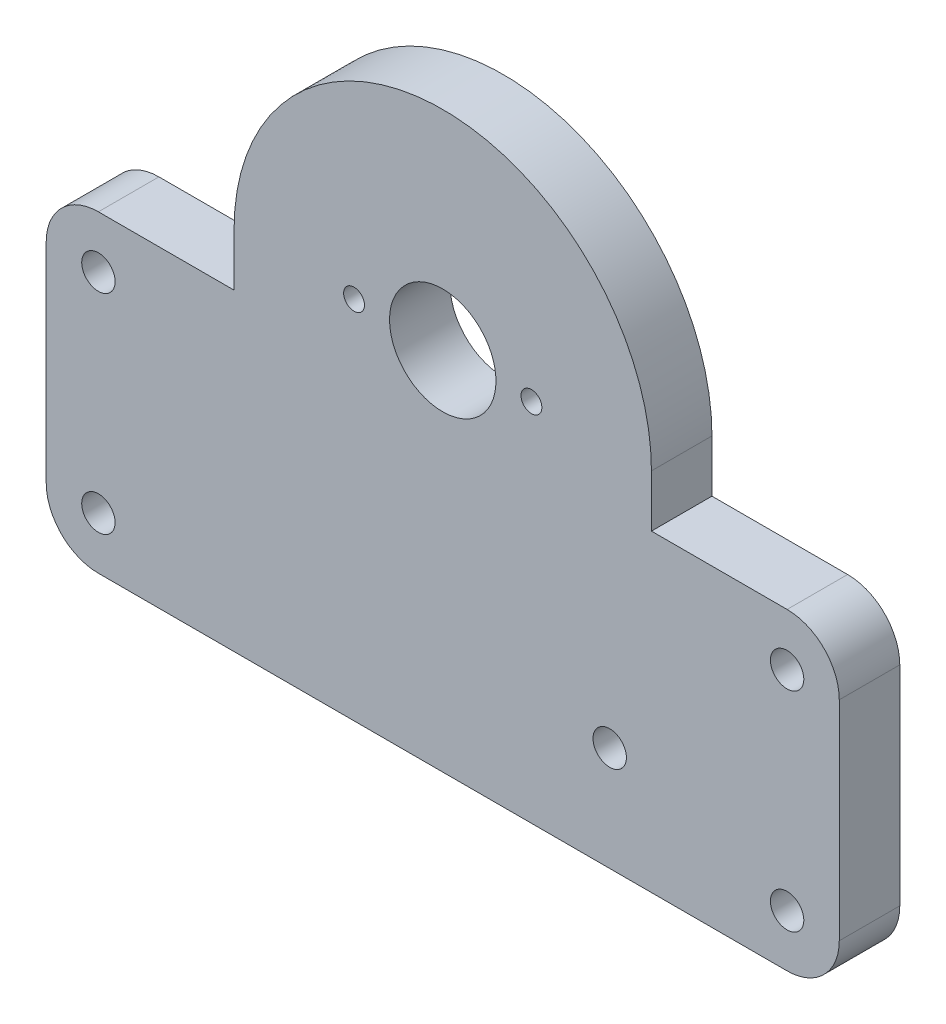
SolidWorks part; units mm, degrees
material "MC901"
ref_plane "正面" through (0, 0, 0) normal (0, 0, 1) x (1, 0, 0)
ref_plane "平面" through (0, 0, 0) normal (0, 1, 0) x (1, 0, 0)
ref_plane "右側面" through (0, 0, 0) normal (1, 0, 0) x (0, 0, -1)
sketch "ｽｹｯﾁ1" plane through (0, 0, 0) normal (0, 0, 1) x (1, 0, 0)
  line L1 (-38, -30) -> (38, -30)
  line L2 (-38, -30) -> (-38, 30)
  line L3 (-38, 30) -> (38, 30)
  line L4 (38, -30) -> (38, 30)
  line L5 (-38, -30) -> (38, 30) construction
  line L6 (-38, 30) -> (38, -30) construction
  point P0 (0, 0)
  dimension "D1" = 76
  dimension "60" = 60
extrude "ﾎﾞｽ - 押し出し3" add sketch "ｽｹｯﾁ1" along normal blind 5.8
sketch "ｽｹｯﾁ4" plane through (0, 0, 0) normal (0, 0, -1) x (-1, 0, 0)
  line L0 (0, 30) -> (0, -30) construction
  line L1 (-38, 30) -> (38, 30) construction
  line L2 (38, -30) -> (-38, -30) construction
  line L3 (-38, 5) -> (38, 5) construction
  line L4 (-38, -30) -> (-38, 30) construction
  line L5 (38, 30) -> (38, -30) construction
  line L6 (-33, 30) -> (-33, -30) construction
  line L7 (33, 30) -> (33, -30) construction
  circle A0 centre (0, 5) radius 5.1
  circle A1 centre (-33, -5) radius 1.6
  circle A2 centre (-33, -25) radius 1.6
  circle A5 centre (33, -25) radius 1.6
  circle A6 centre (33, -5) radius 1.6
  dimension "D2" = 10.2
  dimension "D4" = 35
  dimension "D5" = 5
  dimension "D6" = 3.2
  dimension "D7" = 35
  dimension "D1" = 25
  dimension "D3" = 5
extrude "ｶｯﾄ - 押し出し2" cut sketch "ｽｹｯﾁ4" against normal blind 50
fillet "ﾌｨﾚｯﾄ4" radius 5 4 edges at (-38, 30, 2.9) (-38, -30, 2.9) (38, -30, 2.9) (38, 30, 2.9)
sketch "ｽｹｯﾁ10" plane through (0, 0, 0) normal (0, 0, -1) x (-1, 0, 0)
  line L0 (-38, 0) -> (-20, 0)
  line L1 (-38, -25) -> (-38, 25) construction
  line L2 (-20, 0) -> (-20, 5)
  line L3 (20, 5) -> (20, 0)
  line L4 (20, 0) -> (38, 0)
  line L5 (38, 25) -> (38, -25) construction
  line L6 (38, 0) -> (38, 30)
  line L7 (38, 30) -> (-38, 30)
  line L8 (-38, 30) -> (-38, 0)
  arc A0 (-20, 5) -> (20, 5) centre (0, 5) cw
  dimension "D1" = 20
extrude "ｶｯﾄ - 押し出し7" cut sketch "ｽｹｯﾁ10" against normal blind 13.5
fillet "ﾌｨﾚｯﾄ8" radius 5 2 edges at (-38, 0, 2.9) (38, 0, 2.9)
sketch "ｽｹｯﾁ11" plane through (0, 0, 0) normal (0, 0, -1) x (-1, 0, 0)
  line L0 (-8.5, 5) -> (8.5, 5) construction
  line L1 (0, 5) -> (0, -0.1) construction
  circle A0 centre (0, 5) radius 8.5 construction
  circle A1 centre (-8.5, 5) radius 1
  circle A2 centre (0, 5) radius 5.1 construction
  circle A3 centre (8.5, 5) radius 1
  dimension "D1" = 17
  dimension "D2" = 2
extrude "ｶｯﾄ - 押し出し8" cut sketch "ｽｹｯﾁ11" against normal through all
sketch "ｽｹｯﾁ12" plane through (0, 0, 5.8) normal (0, 0, 1) x (1, 0, 0)
  line L0 (38, -25) -> (38, -5) construction
  line L1 (-33, -30) -> (33, -30) construction
  circle A0 centre (16, -20) radius 1.6
  dimension "D1" = 22
  dimension "D2" = 10
  dimension "D3" = 3.2
extrude "ｶｯﾄ - 押し出し9" cut sketch "ｽｹｯﾁ12" against normal through all
